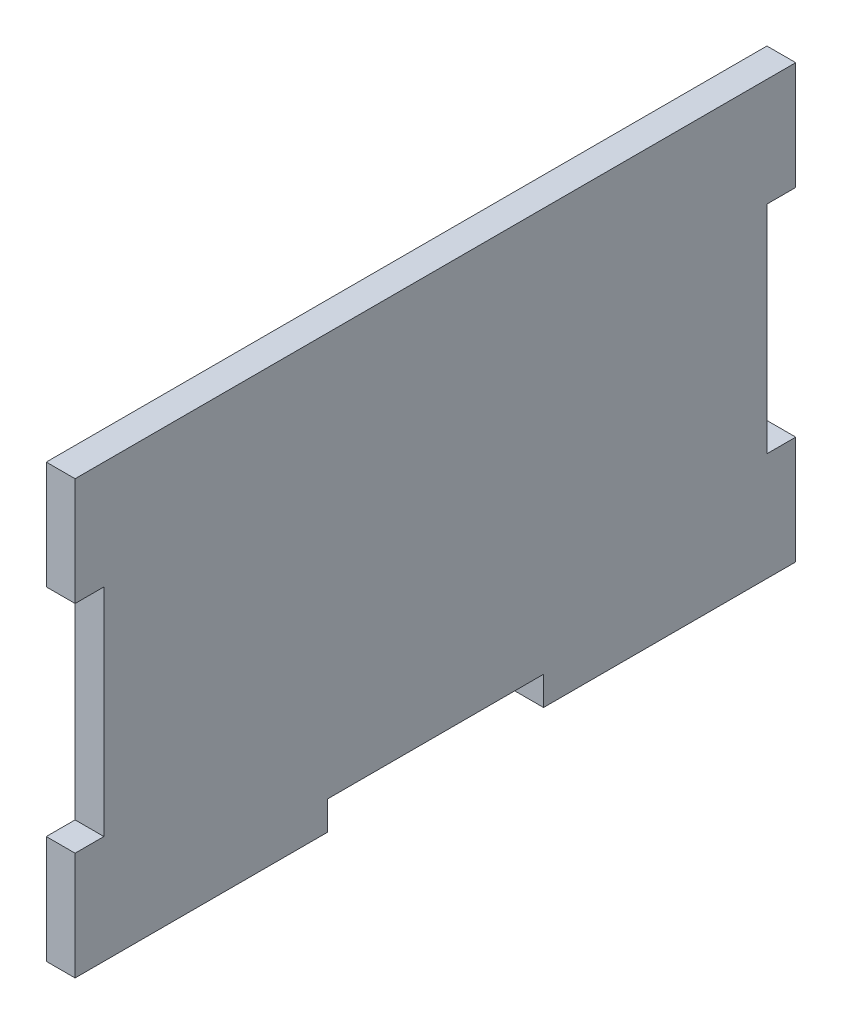
SolidWorks part; units mm, degrees
material "Plastique personnalisé"
ref_plane "Plan de face" through (0, 0, 0) normal (0, 0, 1) x (1, 0, 0)
ref_plane "Plan de dessus" through (0, 0, 0) normal (0, 1, 0) x (1, 0, 0)
ref_plane "Plan de droite" through (0, 0, 0) normal (1, 0, 0) x (0, 0, -1)
sketch "Esquisse1" plane through (0, 0, 0) normal (1, 0, 0) x (0, 0, -1)
  line L1 (0, 0) -> (50, 0)
  line L2 (0, 0) -> (0, 30)
  line L3 (0, 30) -> (50, 30)
  line L4 (50, 0) -> (50, 30)
  dimension "D1" = 30
  dimension "D2" = 50
extrude "Boss.-Extru.1" add sketch "Esquisse1" along normal blind 2
sketch "Esquisse2" plane through (2, 0, 0) normal (1, 0, 0) x (0, 0, -1)
  line L0 (25, 30) -> (25, 0) construction
  line L1 (50, 30) -> (0, 30) construction
  line L2 (0, 0) -> (50, 0) construction
  line L3 (0, 15) -> (50, 15) construction
  line L4 (0, 30) -> (0, 0) construction
  line L5 (50, 0) -> (50, 30) construction
  line L6 (0, 15) -> (0, 30) construction
  line L7 (0, 22.5) -> (2, 22.5)
  line L8 (2, 22.5) -> (2, 7.5)
  line L9 (0, 22.5) -> (0, 7.5)
  line L10 (0, 7.5) -> (2, 7.5)
  line L11 (50, 22.5) -> (50, 7.5)
  line L12 (50, 7.5) -> (48, 7.5)
  line L13 (48, 22.5) -> (48, 7.5)
  line L14 (50, 22.5) -> (48, 22.5)
  point P18 (2, 15)
  dimension "D1" = 2
extrude "Enlèv. mat.-Extru.1" cut sketch "Esquisse2" against normal blind 2
sketch "Esquisse3" plane through (2, 0, 0) normal (1, 0, 0) x (0, 0, -1)
  line L0 (2, 15) -> (48, 15) construction
  line L1 (2, 7.5) -> (2, 22.5) construction
  line L2 (48, 22.5) -> (48, 7.5) construction
  line L3 (48, 15) -> (25, 15) construction
  line L4 (25, 15) -> (25, 30) construction
  line L5 (50, 30) -> (0, 30) construction
  line L6 (25, 15) -> (25, 0) construction
  line L7 (0, 0) -> (50, 0) construction
  line L8 (32.5026, 0) -> (17.4974, 0)
  line L9 (17.4974, 0) -> (17.4974, 2)
  line L10 (17.4974, 2) -> (32.5026, 2)
  line L11 (32.5026, 0) -> (32.5026, 2)
  point P17 (25, 2)
  dimension "D1" = 2
extrude "Enlèv. mat.-Extru.2" cut sketch "Esquisse3" against normal blind 2
